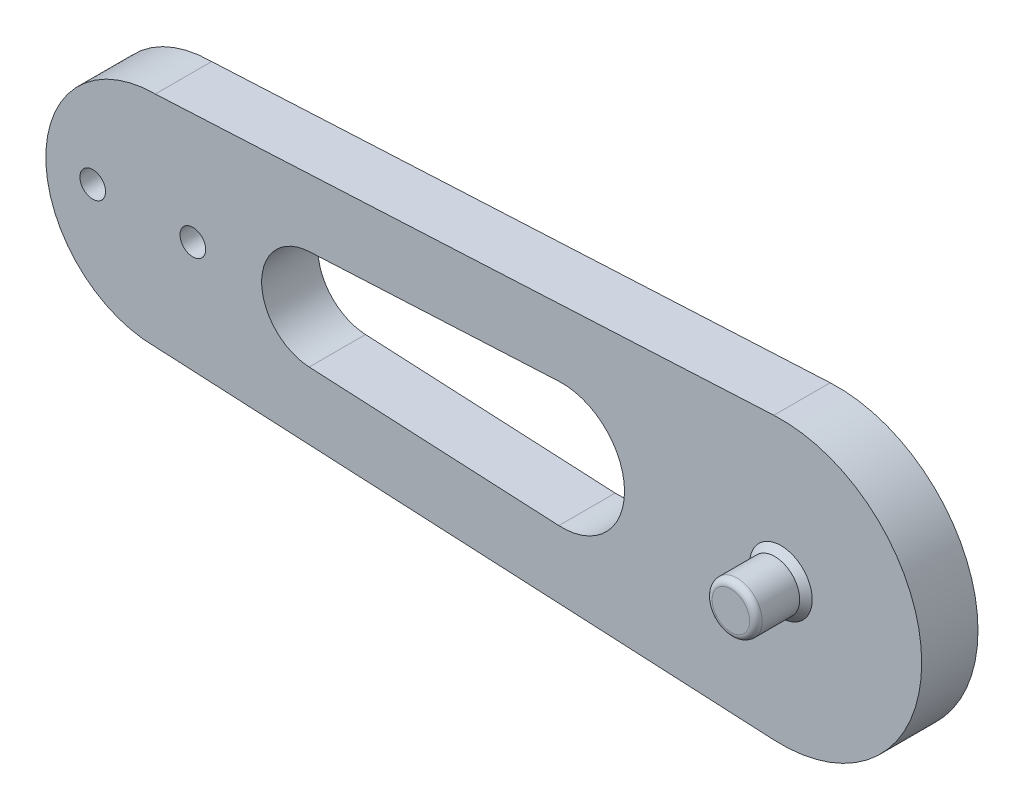
SolidWorks part; units mm, degrees
ref_plane "Front Plane" through (0, 0, 0) normal (1, 0, 0) x (0, 1, 0)
ref_plane "Top Plane" through (0, 0, 0) normal (0, 0, 1) x (0, 1, 0)
ref_plane "Right Plane" through (0, 0, 0) normal (0, 1, 0) x (-1, 0, 0)
sketch "Sketch2" plane through (0, 0, 0) normal (0, 0, 1) x (0, 1, 0)
  line L0 (22.4716, 1.13) -> (17.5, 100)
  line L1 (-22.4716, 1.13) -> (-17.5, 100)
  arc A0 (-22.4716, 1.13) -> (22.4716, 1.13) centre (0, 0) ccw
  arc A2 (17.5, 100) -> (-17.5, 100) centre (0, 100) ccw
  dimension "D1" = 45
  dimension "D3" = 35
  dimension "D4" = 100
extrude "Boss-Extrude1" add sketch "Sketch2" along normal blind 9
sketch "Sketch3" plane through (0, 0, 0) normal (0, 0, 1) x (0, 1, 0)
  circle A0 centre (0, 0) radius 4
  dimension "D1" = 8
extrude "Boss-Extrude2" add sketch "Sketch3" along normal blind 8 from surface at 9 starting at face at (-49.0325, 0, 9)
fillet "Fillet1" radius 1 1 edges at (4, 0, 17)
chamfer "Chamfer2" distance 1 angle 45 1 edges at (4, 0, 9)
sketch "Sketch5" plane through (0, 0, 0) normal (0, 0, 1) x (0, 1, 0)
  line L0 (0, 0) -> (11.8394, 0) construction
  line L1 (-2.6771, -18.8507) -> (-4.65, -3.7918)
  line L2 (0, 0) -> (0, -3.0795) construction
  line L3 (2.6771, -18.8507) -> (4.65, -3.7918)
  line L4 (-2.6771, 18.8507) -> (-4.65, 3.7918)
  line L5 (2.6771, 18.8507) -> (4.65, 3.7918)
  arc A0 (4.65, -3.7918) -> (4.65, 3.7918) centre (0, 0) ccw
  arc A1 (-2.6771, -18.8507) -> (2.6771, -18.8507) centre (0, -18.5) ccw
  arc A2 (-2.6771, 18.8507) -> (2.6771, 18.8507) centre (0, 18.5) cw
  arc A3 (-4.65, 3.7918) -> (-4.65, -3.7918) centre (0, 0) ccw
  dimension "D1" = 12
  dimension "D3" = 5.4
  dimension "D2" = 37
  dimension "D4" = 9.3
extrude "Cut-Extrude1" cut sketch "Sketch5" along normal blind 6 from surface at 0 starting at face at (-49.0325, 0, 0)
fillet "Fillet3" radius 1 8 edges at (11.3212, 3.6636, 0) (0, 6, 0) (-11.3212, 3.6636, 0) (-21.2, 0, 0) (-11.3212, -3.6636, 0) (0, -6, 0) (21.2, 0, 0) (11.3212, -3.6636, 0)
sketch "Sketch6" plane through (0, 0, 0) normal (0, 0, 1) x (0, 1, 0)
  line L0 (0, 0) -> (0, 25.3488) construction
  line L1 (-7.99, 75.4) -> (-9.9875, 35.5)
  line L2 (7.99, 75.4) -> (9.9875, 35.5)
  circle A0 centre (0, 110) radius 2.05
  circle A1 centre (0, 94) radius 2.05
  arc A2 (-9.9875, 35.5) -> (9.9875, 35.5) centre (0, 35) ccw
  arc A3 (7.99, 75.4) -> (-7.99, 75.4) centre (0, 75) ccw
  dimension "D1" = 4.1
  dimension "D2" = 4.1
  dimension "D5" = 16
  dimension "D6" = 20
  dimension "D3" = 110
  dimension "D4" = 16
  dimension "D7" = 40
  dimension "D8" = 35
extrude "Cut-Extrude2" cut sketch "Sketch6" along normal blind 10
